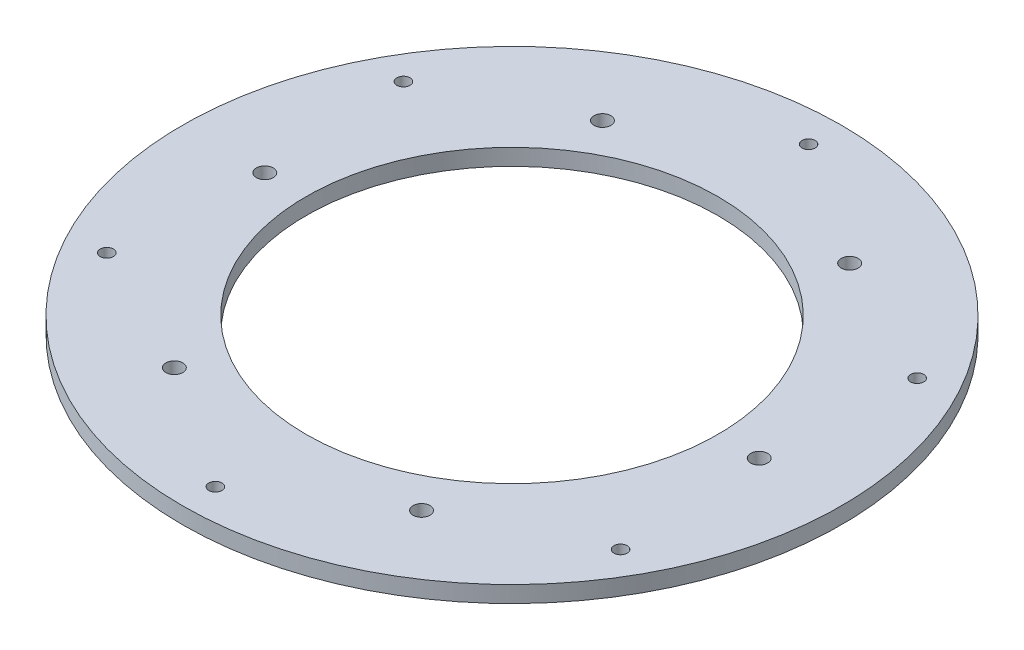
SolidWorks part; units mm, degrees
ref_plane "前视基准面" through (0, 0, 0) normal (0, 0, 1) x (1, 0, 0)
ref_plane "上视基准面" through (0, 0, 0) normal (0, 1, 0) x (1, 0, 0)
ref_plane "右视基准面" through (0, 0, 0) normal (1, 0, 0) x (0, 0, -1)
sketch "草图1" plane through (0, 0, 0) normal (0, 1, 0) x (1, 0, 0)
  line L0 (0, 0) -> (-62.3538, 36) construction
  line L1 (0, 0) -> (-60, 0) construction
  circle A0 centre (0, 0) radius 50
  circle A1 centre (0, 0) radius 80
  circle A2 centre (60, 0) radius 2.05
  circle A3 centre (30, -51.9615) radius 2.05
  circle A4 centre (-30, -51.9615) radius 2.05
  circle A5 centre (-60, 0) radius 2.05
  circle A6 centre (-30, 51.9615) radius 2.05
  circle A7 centre (30, 51.9615) radius 2.05
  circle A9 centre (-62.3538, 36) radius 2.05
  circle A10 centre (0, 72) radius 2.05
  circle A11 centre (62.3538, 36) radius 2.05
  circle A12 centre (62.3538, -36) radius 2.05
  circle A13 centre (0, -72) radius 2.05
  circle A14 centre (-62.3538, -36) radius 2.05
  point P18 (0, 0)
  point P31 (0, 0)
  dimension "D1" = 100
  dimension "D2" = 160
  dimension "D4" = 6
  dimension "D5" = 4.1
  dimension "D7" = 72
  dimension "D8" = 6
  dimension "D3" = 60
  dimension "D6" = 30
extrude "凸台-拉伸1" add sketch "草图1" along normal blind 4
sketch "草图2" plane through (0, 4, 0) normal (0, 1, 0) x (1, 0, 0)
  circle A0 centre (62.3538, 36) radius 2.05 construction
  circle A1 centre (62.3538, -36) radius 2.05 construction
  circle A2 centre (0, -72) radius 2.05 construction
  circle A3 centre (-62.3538, -36) radius 2.05 construction
  circle A4 centre (-62.3538, 36) radius 2.05 construction
  circle A5 centre (0, 72) radius 2.05 construction
  circle A6 centre (62.3538, 36) radius 2.05
  circle A7 centre (62.3538, -36) radius 2.05
  circle A8 centre (0, -72) radius 2.05
  circle A9 centre (-62.3538, -36) radius 2.05
  circle A10 centre (-62.3538, 36) radius 2.05
  circle A11 centre (0, 72) radius 2.05
  circle A12 centre (0, 72) radius 1.6
  circle A13 centre (62.3538, 36) radius 1.6
  circle A14 centre (62.3538, -36) radius 1.6
  circle A15 centre (0, -72) radius 1.6
  circle A16 centre (-62.3538, -36) radius 1.6
  circle A17 centre (-62.3538, 36) radius 1.6
  dimension "D1" = 3.2
extrude "凸台-拉伸2" add sketch "草图2" against normal up to surface (4 mm away) up to face at (0, 0, 80)
